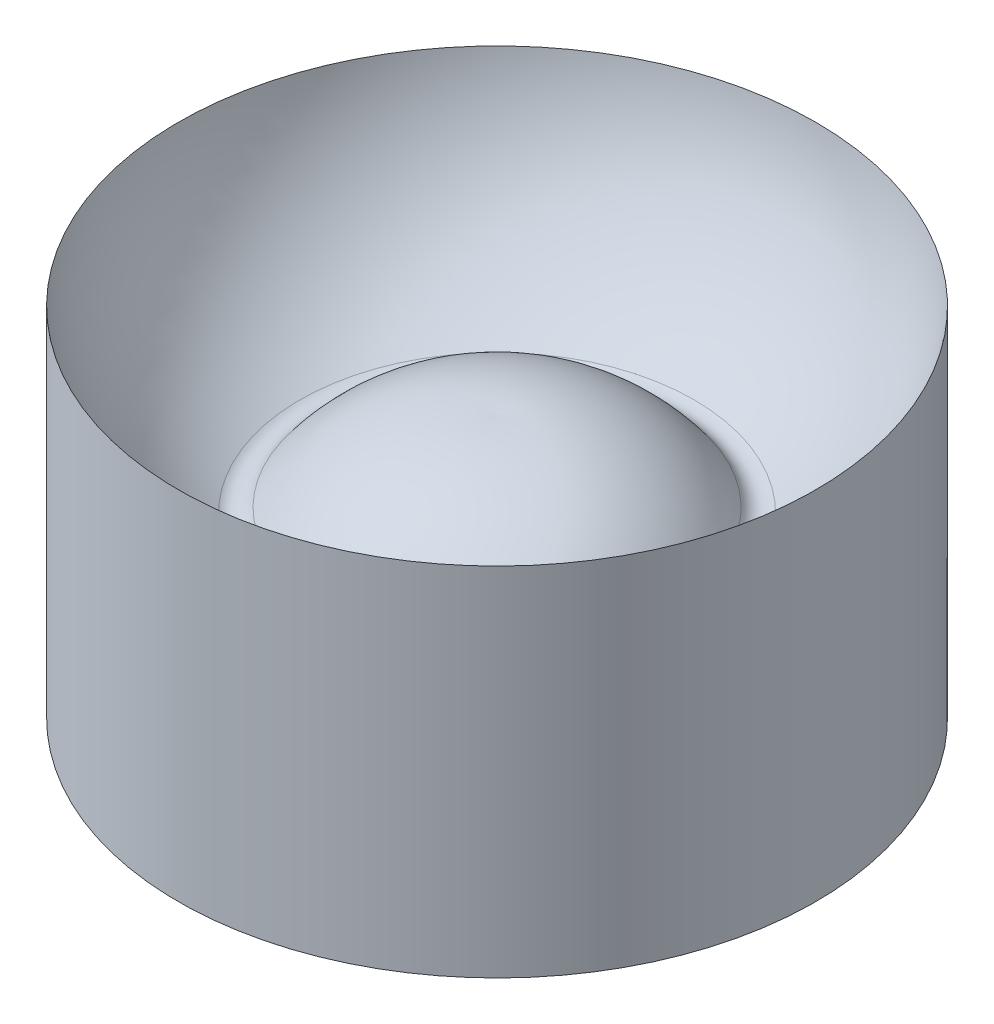
SolidWorks part; units mm, degrees
material "PET"
ref_plane "Front Plane" through (0, 0, 0) normal (0, 0, 1) x (1, 0, 0)
ref_plane "Top Plane" through (0, 0, 0) normal (0, 1, 0) x (1, 0, 0)
ref_plane "Right Plane" through (0, 0, 0) normal (1, 0, 0) x (0, 0, -1)
sketch "Sketch1" plane through (0, 0, 0) normal (0, 0, 1) x (1, 0, 0)
  line L0 (-0.0199, 35.9867) -> (-0.0199, 36.8883)
  line L1 (50.9, -7) -> (50.9, -27)
  line L2 (0, 0) -> (0, 15)
  line L5 (50.9, 0) -> (50.9, 30)
  line L6 (0, 0) -> (0, -7)
  line L7 (0, -7) -> (47.9, -7)
  line L8 (50.9, -7) -> (50.9, 0)
  line L9 (50.9, -27) -> (47.9, -27)
  line L10 (47.9, -27) -> (47.9, -7)
  arc A10 (27.5748, 2.1315) -> (0, 15) centre (2.1233, -16.4284) ccw
  arc A11 (31.4777, 1.289) -> (50.9, 30) centre (12.251, 35.2203) ccw
  arc A12 (31.4777, 1.289) -> (27.5748, 2.1315) centre (29.9988, 3.8991) cw
  point P36 (29, 0)
  dimension "D2" = 20
  dimension "D3" = 3
  dimension "D7" = 31.5
  dimension "D10" = 39
  dimension "D12" = 3
  dimension "D5" = 15
  dimension "D6" = 29
  dimension "D8" = 21.9
  dimension "D9" = 30
  dimension "D11" = 7
revolve "Revolve1" add sketch "Sketch1" angle 360 about L2
sketch "Sketch2" plane through (0, -7, 0) normal (0, -1, 0) x (1, 0, 0)
  line L0 (7.7646, -28.9778) -> (9.5763, -35.7393)
  line L1 (-7.7646, -28.9778) -> (-9.5763, -35.7393)
  line L2 (28.9778, 7.7646) -> (35.7393, 9.5763)
  line L3 (28.9778, -7.7646) -> (35.7393, -9.5763)
  line L4 (-28.9778, -7.7646) -> (-35.7393, -9.5763)
  line L5 (-28.9778, 7.7646) -> (-35.7393, 9.5763)
  line L6 (-7.7646, 28.9778) -> (-9.5763, 35.7393)
  line L7 (7.7646, 28.9778) -> (9.5763, 35.7393)
  arc A0 (28.9778, -7.7646) -> (28.9778, 7.7646) centre (0, 0) ccw
  arc A1 (35.7393, -9.5763) -> (35.7393, 9.5763) centre (0, 0) ccw
  arc A2 (-9.5763, -35.7393) -> (9.5763, -35.7393) centre (0, 0) ccw
  arc A3 (-7.7646, -28.9778) -> (7.7646, -28.9778) centre (0, 0) ccw
  arc A4 (-35.7393, 9.5763) -> (-35.7393, -9.5763) centre (0, 0) ccw
  arc A5 (-28.9778, 7.7646) -> (-28.9778, -7.7646) centre (0, 0) ccw
  arc A6 (9.5763, 35.7393) -> (-9.5763, 35.7393) centre (0, 0) ccw
  arc A7 (7.7646, 28.9778) -> (-7.7646, 28.9778) centre (0, 0) ccw
  point P21 (0, 0)
  dimension "D1" = 4
extrude "Boss-Extrude1" add sketch "Sketch2" along normal blind 17
ref_plane "Plane1" through (0, -12, 0) normal (0, -1, 0) x (-1, 0, 0)
sketch "Sketch3" plane through (0, -12, 0) normal (0, -1, 0) x (-1, 0, 0)
  line L0 (3.7779, -30.7689) -> (4.3873, -35.7317)
  line L1 (30.7689, 3.7779) -> (35.7317, 4.3873)
  line L2 (29.9437, -8.0234) -> (34.7733, -9.3175)
  line L3 (-8.0234, -29.9437) -> (-9.3175, -34.7733)
  line L4 (-30.7689, -3.7779) -> (-35.7317, -4.3873)
  line L5 (-29.9437, 8.0234) -> (-34.7733, 9.3175)
  line L6 (-3.7779, 30.7689) -> (-4.3873, 35.7317)
  line L7 (8.0234, 29.9437) -> (9.3175, 34.7733)
  arc A1 (29.9437, -8.0234) -> (30.7689, 3.7779) centre (0, 0) ccw
  arc A2 (34.7733, -9.3175) -> (35.7317, 4.3873) centre (0, 0) ccw
  arc A3 (-9.3175, -34.7733) -> (4.3873, -35.7317) centre (0, 0) ccw
  arc A4 (-8.0234, -29.9437) -> (3.7779, -30.7689) centre (0, 0) ccw
  arc A5 (-34.7733, 9.3175) -> (-35.7317, -4.3873) centre (0, 0) ccw
  arc A6 (-29.9437, 8.0234) -> (-30.7689, -3.7779) centre (0, 0) ccw
  arc A7 (9.3175, 34.7733) -> (-4.3873, 35.7317) centre (0, 0) ccw
  arc A8 (8.0234, 29.9437) -> (-3.7779, 30.7689) centre (0, 0) ccw
  point P23 (0, 0)
  dimension "D1" = 62
  dimension "D2" = 72
  dimension "D3" = 4
extrude "Cut-Extrude1" cut sketch "Sketch3" along normal blind 7
